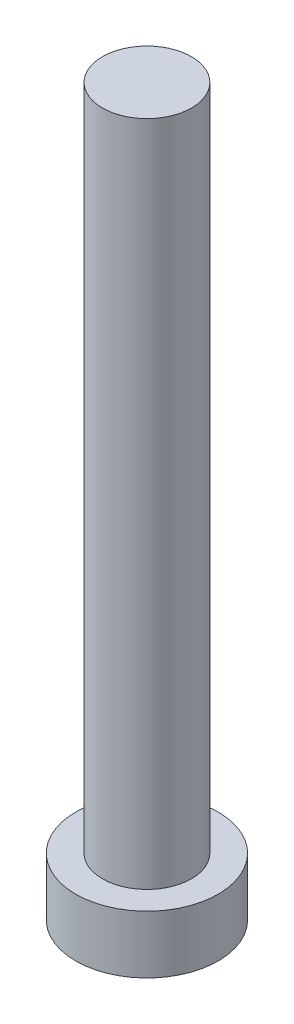
SolidWorks part; units mm, degrees
ref_plane "前视基准面" through (0, 0, 0) normal (0, 0, 1) x (1, 0, 0)
ref_plane "上视基准面" through (0, 0, 0) normal (0, 1, 0) x (1, 0, 0)
ref_plane "右视基准面" through (0, 0, 0) normal (1, 0, 0) x (0, 0, -1)
other "Configuration Table"
sketch "草图1" plane through (0, 0, 0) normal (0, 1, 0) x (1, 0, 0)
  circle A0 centre (0, 0) radius 1.6
  dimension "D1" = 3.2
extrude "凸台-拉伸1" add sketch "草图1" along normal blind 1.3
sketch "草图2" plane through (0, 0, 0) normal (0, 1, 0) x (1, 0, 0)
  circle A0 centre (0, 0) radius 1
extrude "凸台-拉伸2" add sketch "草图2" along normal blind 15 from surface at 1.3 starting at face at (0, 1.3, 1.6)
